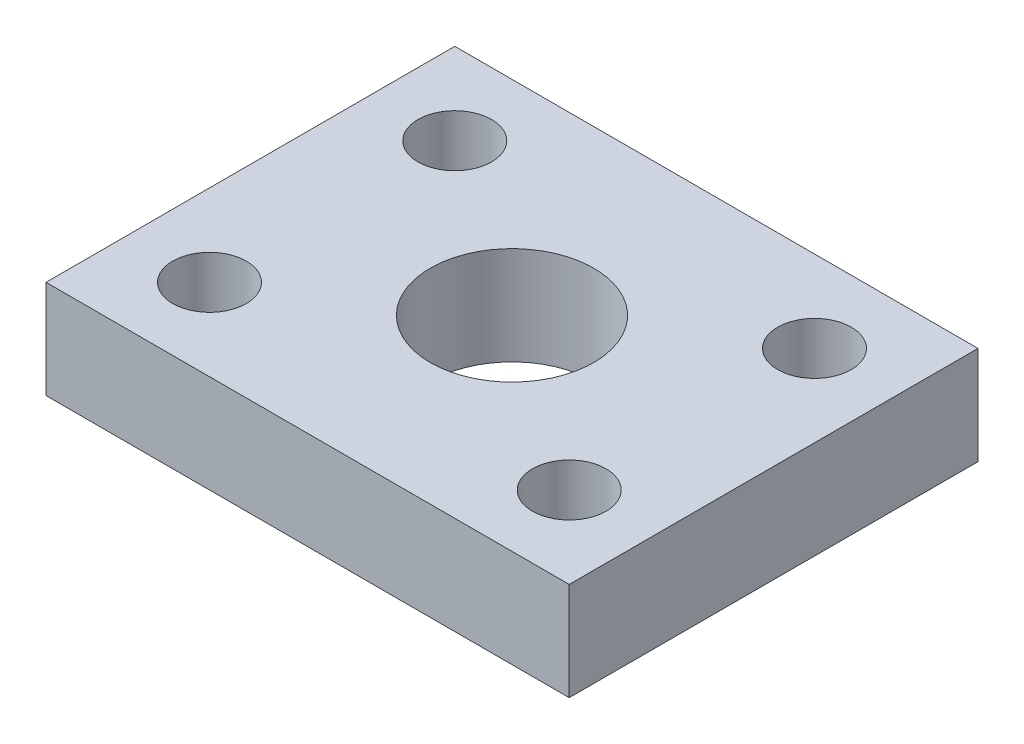
SolidWorks part; units mm, degrees
material "Printed PLA"
ref_plane "Front Plane" through (0, 0, 0) normal (0, 0, 1) x (1, 0, 0)
ref_plane "Top Plane" through (0, 0, 0) normal (0, 1, 0) x (1, 0, 0)
ref_plane "Right Plane" through (0, 0, 0) normal (1, 0, 0) x (0, 0, -1)
sketch "Sketch1" plane through (0, 0, 0) normal (0, 1, 0) x (1, 0, 0)
  line L0 (-11, 7.5) -> (11, -7.5) construction
  line L1 (-16, 12.5) -> (16, 12.5)
  line L2 (-16, 12.5) -> (-16, -12.5)
  line L3 (-16, -12.5) -> (16, -12.5)
  line L4 (16, 12.5) -> (16, -12.5)
  line L5 (-11, 7.5) -> (11, 7.5) construction
  line L6 (-11, 7.5) -> (-11, -7.5) construction
  line L7 (-11, -7.5) -> (11, -7.5) construction
  line L8 (11, 7.5) -> (11, -7.5) construction
  line L9 (-16, -12.5) -> (16, 12.5) construction
  circle A0 centre (11, 7.5) radius 2.25
  circle A1 centre (11, -7.5) radius 2.25
  circle A2 centre (-11, -7.5) radius 2.25
  circle A3 centre (-11, 7.5) radius 2.25
  circle A4 centre (0, 0) radius 5
  dimension "D2" = 4.5
  dimension "D6" = 10
  dimension "D1" = 22
  dimension "D3" = 15
  dimension "D4" = 32
  dimension "D5" = 25
extrude "Boss-Extrude1" add sketch "Sketch1" along normal blind 6
